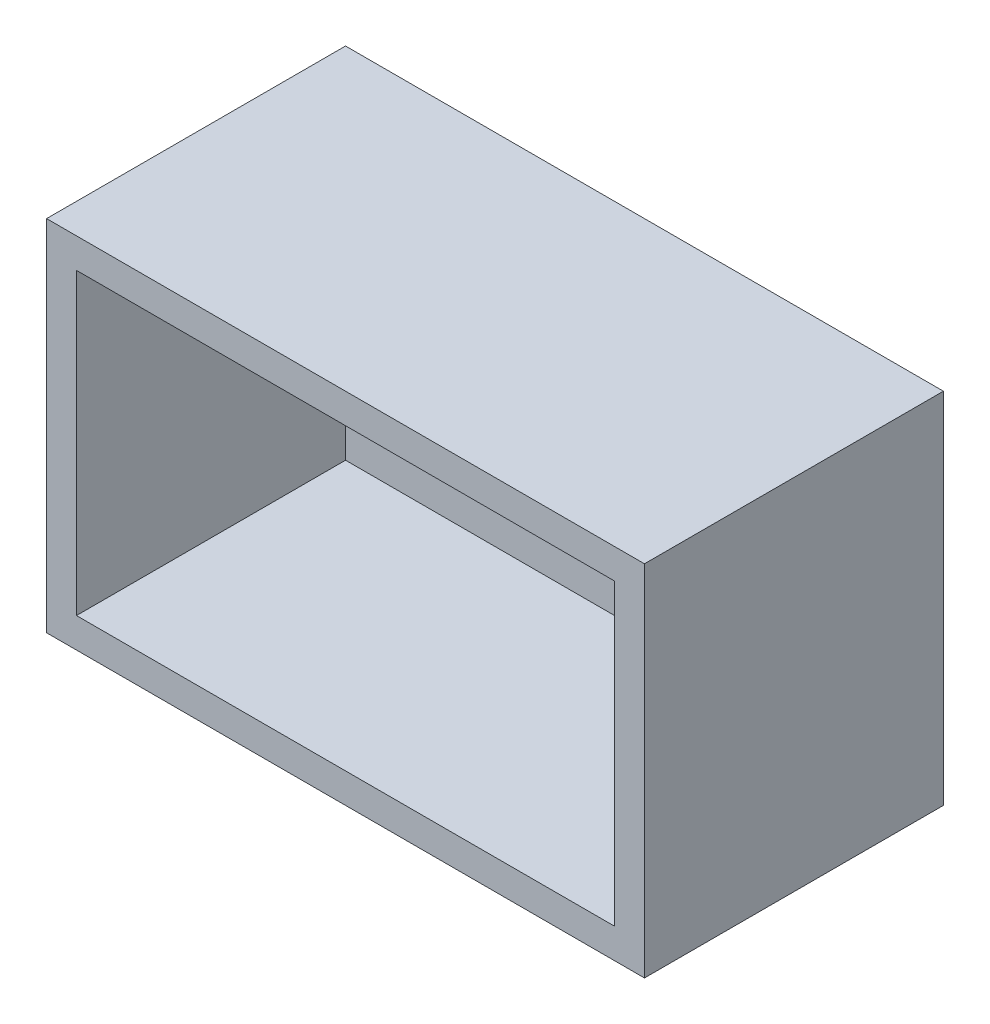
SolidWorks part; units mm, degrees
ref_plane "前视基准面" through (0, 0, 0) normal (0, 0, 1) x (1, 0, 0)
ref_plane "上视基准面" through (0, 0, 0) normal (0, 1, 0) x (1, 0, 0)
ref_plane "右视基准面" through (0, 0, 0) normal (1, 0, 0) x (0, 0, -1)
sketch "草图1" plane through (0, 0, 0) normal (0, 0, 1) x (1, 0, 0)
  line L0 (-50, -30) -> (50, -30)
  line L1 (50, -30) -> (50, 30)
  line L2 (50, 30) -> (-50, 30)
  line L3 (-50, 30) -> (-50, -30)
extrude "凸台-拉伸1" add sketch "草图1" along normal blind 50
shell "抽壳1" thickness 5
